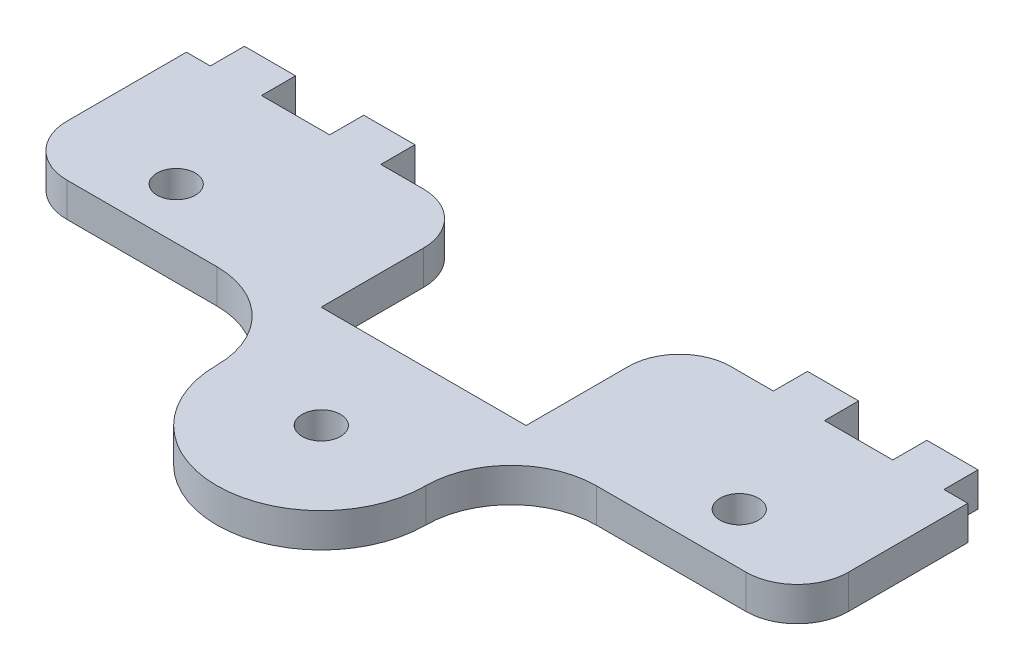
SolidWorks part; units mm, degrees
ref_plane "Front" through (0, 0, 0) normal (0, 0, 1) x (1, 0, 0)
ref_plane "Top" through (0, 0, 0) normal (0, 1, 0) x (1, 0, 0)
ref_plane "Right" through (0, 0, 0) normal (1, 0, 0) x (0, 0, -1)
sketch "Croquis1" plane through (0, 0, 0) normal (0, 1, 0) x (1, 0, 0)
  line L0 (-776.5744, 0) -> (38052.1471, 0) construction
  line L1 (0, -776.5744) -> (0, 38052.1471) construction
  line L2 (19.91, 0) -> (11.125, 0)
  line L3 (-22.91, 3) -> (-22.91, 10)
  line L4 (-22.91, 10) -> (-21.51, 10)
  line L5 (-14.51, 10) -> (-14.51, 12)
  line L6 (-14.51, 12) -> (-11.51, 12)
  line L7 (-11.51, 12) -> (-11.51, 10)
  line L8 (-11.51, 10) -> (-9.01, 10)
  line L9 (-6.01, 7) -> (-6.01, 1)
  line L10 (-6.01, 1) -> (6.01, 1)
  line L11 (6.01, 7) -> (6.01, 1)
  line L12 (11.51, 10) -> (9.01, 10)
  line L13 (11.51, 12) -> (11.51, 10)
  line L14 (14.51, 12) -> (11.51, 12)
  line L15 (14.51, 10) -> (14.51, 12)
  line L16 (22.91, 10) -> (21.51, 10)
  line L17 (22.91, 3) -> (22.91, 10)
  line L18 (-1000, 2) -> (49000, 2) construction
  line L19 (-11.125, 0) -> (-19.91, 0)
  line L20 (-13.01, -988) -> (-13.01, 49012) construction
  line L21 (-16.51, -988) -> (-16.51, 49012) construction
  line L22 (-18.51, 10) -> (-18.51, 12)
  line L23 (-18.51, 12) -> (-21.51, 12)
  line L24 (-21.51, 12) -> (-21.51, 10)
  line L25 (-18.51, 10) -> (-14.51, 10)
  line L26 (18.51, 10) -> (18.51, 12)
  line L27 (18.51, 12) -> (21.51, 12)
  line L28 (21.51, 12) -> (21.51, 10)
  line L29 (18.51, 10) -> (14.51, 10)
  circle A0 centre (-16.51, 3) radius 1.125
  arc A1 (-19.91, 0) -> (-22.91, 3) centre (-19.91, 3) cw
  circle A2 centre (16.51, 3) radius 1.125
  arc A3 (19.91, 0) -> (22.91, 3) centre (19.91, 3) ccw
  arc A4 (6.01, 7) -> (9.01, 10) centre (9.01, 7) cw
  arc A5 (-6.01, 7) -> (-9.01, 10) centre (-9.01, 7) ccw
  circle A7 centre (0, -5) radius 1.125
  arc A9 (11.125, 0) -> (6.125, -5) centre (11.125, -5) ccw
  arc A10 (-11.125, 0) -> (-6.125, -5) centre (-11.125, -5) cw
  arc A11 (-6.125, -5) -> (6.125, -5) centre (0, -5) ccw
  point P16 (0, 4)
  point P23 (0, 0)
  point P25 (-22.91, 10)
  point P28 (-22.91, 0)
  point P30 (-13.01, 12)
  point P31 (22.91, 10)
  point P34 (22.91, 0)
  point P37 (6.01, 10)
  point P40 (-6.01, 10)
  point P52 (6.125, -5)
  point P58 (22.0313, 0.8787)
  point P66 (0, 1)
  dimension "D9" = 7
  dimension "D10" = 3
  dimension "D11" = 3.5
  dimension "D12" = 3
  dimension "D13" = 3
  dimension "D15" = 6.4
  dimension "D16" = 7
  dimension "D17" = 2.25
  dimension "D14" = 2.25
  dimension "D20" = 10
  dimension "D21" = 3
  dimension "D4" = 1
  dimension "D1" = 22.91
  dimension "D2" = 10
  dimension "D3" = 8.4
  dimension "D5" = 2
  dimension "D6" = 3
  dimension "D7" = 6
  dimension "D8" = 5.5
  dimension "D18" = 5
extrude "Saliente-Extruir1" add sketch "Croquis1" along normal blind 2
sketch "Croquis2" plane through (0, 2, 0) normal (0, 1, 0) x (1, 0, 0)
  line L0 (0, -1000) -> (0, 49000) construction
  line L1 (14.51, 10) -> (11.51, 10)
  line L2 (-14.51, 12) -> (-11.51, 12)
  line L3 (-14.51, 12) -> (-14.51, 10)
  line L4 (-14.51, 10) -> (-11.51, 10)
  line L5 (-11.51, 12) -> (-11.51, 10)
  line L6 (11.51, 12) -> (11.51, 10)
  line L7 (14.51, 12) -> (11.51, 12)
  line L8 (14.51, 12) -> (14.51, 10)
  line L9 (-13.01, -988) -> (-13.01, 49012) construction
  line L10 (-16.51, -988) -> (-16.51, 49012) construction
  line L11 (-21.51, 12) -> (-21.51, 10)
  line L12 (-18.51, 12) -> (-21.51, 12)
  line L13 (-18.51, 12) -> (-18.51, 10)
  line L14 (-18.51, 10) -> (-21.51, 10)
  line L15 (21.51, 12) -> (21.51, 10)
  line L16 (18.51, 10) -> (21.51, 10)
  line L17 (18.51, 12) -> (18.51, 10)
  line L18 (18.51, 12) -> (21.51, 12)
  point P18 (-13.01, 12)
  dimension "D1" = 3.5
extrude "Cortar-Extruir1" [suppressed] cut sketch "Croquis2" against normal blind 1
sketch "Croquis3" plane through (0, 0, 0) normal (0, -1, 0) x (1, 0, 0)
  line L0 (0, -1000) -> (0, 49000) construction
  line L1 (-1000, 0) -> (49000, 0) construction
  line L2 (-1000, -5.5) -> (49000, -5.5) construction
  line L3 (-22.91, -10) -> (-22.91, -3) construction
  line L4 (-20.01, -5.5) -> (-13.01, -5.5)
  line L5 (-20.01, -5.5) -> (-20.01, -8)
  line L6 (-20.01, -8) -> (-13.01, -8)
  line L7 (-13.01, -5.5) -> (-13.01, -8)
  line L8 (-20.01, -1012) -> (-20.01, 48988) construction
  line L9 (-18.51, -12) -> (-21.51, -12) construction
  line L10 (-13.01, -1012) -> (-13.01, 48988) construction
  line L11 (-11.51, -12) -> (-14.51, -12) construction
  line L14 (20.01, -8) -> (13.01, -8)
  line L15 (13.01, -5.5) -> (13.01, -8)
  line L16 (20.01, -5.5) -> (13.01, -5.5)
  line L17 (20.01, -5.5) -> (20.01, -8)
  point P18 (-20.01, -12)
  point P23 (-13.01, -12)
  dimension "D2" = 7
  dimension "D3" = 2.5
  dimension "D4" = 2.9
  dimension "D1" = 5.5
extrude "Saliente-Extruir2" add sketch "Croquis3" along normal blind 2
